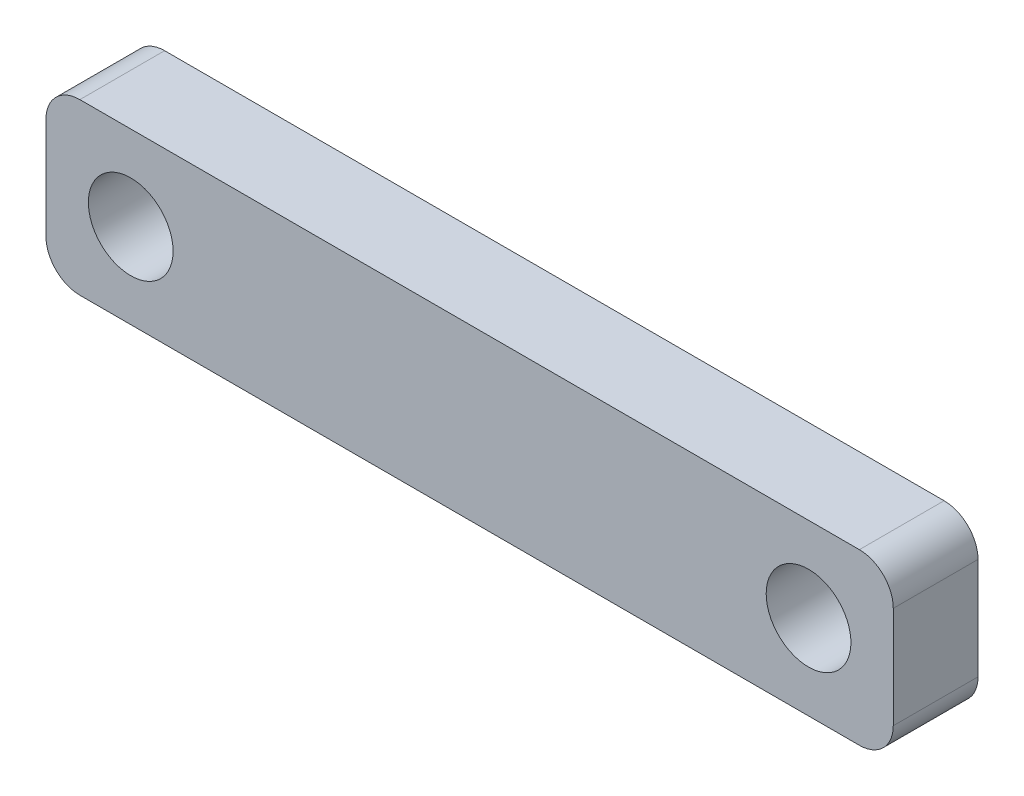
SolidWorks part; units mm, degrees
ref_plane "Plan de face" through (0, 0, 0) normal (0, 0, 1) x (1, 0, 0)
ref_plane "Plan de dessus" through (0, 0, 0) normal (0, 1, 0) x (1, 0, 0)
ref_plane "Plan de droite" through (0, 0, 0) normal (1, 0, 0) x (0, 0, -1)
sketch "Esquisse1" plane through (0, 0, 0) normal (0, 0, 1) x (1, 0, 0)
  line L0 (-16.3416, 3.3696) -> (33.6584, 3.3696) construction
  line L1 (-16.3416, 8.3696) -> (33.6584, 8.3696)
  line L2 (-16.3416, 8.3696) -> (-16.3416, -1.6304)
  line L3 (-16.3416, -1.6304) -> (33.6584, -1.6304)
  line L4 (33.6584, 8.3696) -> (33.6584, -1.6304)
  line L5 (-16.3416, 3.3696) -> (-11.3416, 3.3696) construction
  line L6 (8.6584, 8.3696) -> (8.6584, -1.6304) construction
  circle A0 centre (-11.3416, 3.3696) radius 2.5
  circle A1 centre (28.6584, 3.3696) radius 2.5
  dimension "D1" = 50
  dimension "D2" = 10
  dimension "D3" = 5
extrude "Boss.-Extru.1" add sketch "Esquisse1" along normal blind 5
fillet "Congé1" radius 2 1 edges at (-16.3416, 8.3696, 2.5)
fillet "Congé2" radius 2 1 edges at (-16.3416, -1.6304, 2.5)
fillet "Congé3" radius 2 1 edges at (33.6584, 8.3696, 2.5)
fillet "Congé4" radius 2 1 edges at (33.6584, -1.6304, 2.5)
